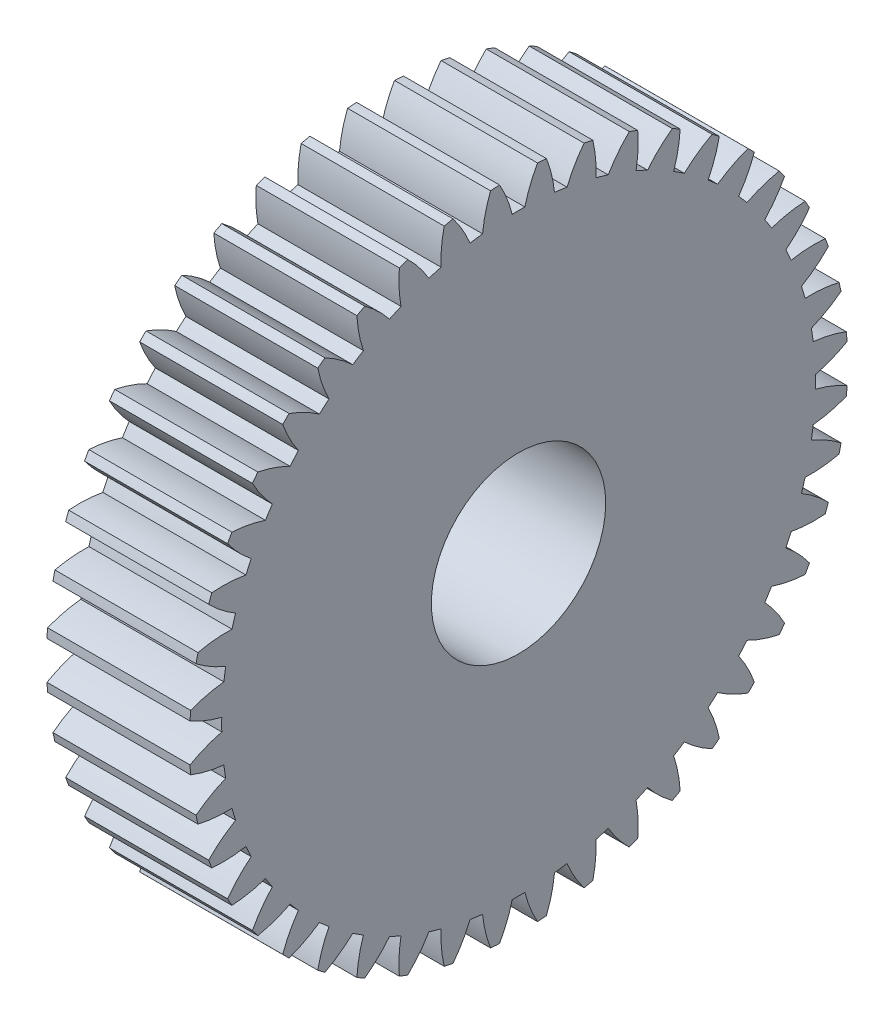
SolidWorks part; units mm, degrees
ref_plane "Plane1" through (0, 0, 0) normal (0, 0, 1) x (1, 0, 0)
ref_plane "Plane2" through (0, 0, 0) normal (0, 1, 0) x (1, 0, 0)
ref_plane "Plane3" through (0, 0, 0) normal (1, 0, 0) x (0, 0, -1)
other "Configuration Table"
sketch "HoldingSke" plane through (0, 0, 0) normal (0, 1, 0) x (1, 0, 0)
  line L0 (0, 0) -> (1.7983, -1.7366)
  line L1 (-15, 0) -> (100, 0) construction
  line L2 (0, 0) -> (-2.1039, 2.3779)
  line L3 (0, 0) -> (-11.863, 4.5341)
  line L4 (0, 0) -> (6.2122, 5.9991)
  line L5 (0, 0) -> (-46.8476, -17.4728)
  line L6 (0, 0) -> (-3.3159, -2.2372)
  line L7 (-2.1039, 2.3779) -> (8.6586, 51.2059)
  line L8 (-76.2, 54.61) -> (-76.1, 54.61)
  line L9 (-71.009, 38.7566) -> (-53.1078, 45.2721)
  line L10 (-76.2, 71.12) -> (104.1128, 71.12)
  line L11 (0, 0) -> (-4, 0)
  line L12 (-76.2, 101.6) -> (-76.185, 101.6)
  line L13 (24.9733, 27.94) -> (52.9518, 28.4284)
  line L14 (24.9733, 27.94) -> (24.9743, 27.94)
  line L15 (24.9733, 27.94) -> (100.4006, 29.5858)
  line L16 (-63.627, -0.4) -> (-12.827, -0.4)
  circle A0 centre (0, 0) radius 0.5
  circle A1 centre (0, 0) radius 8.299
  circle A2 centre (0, 0) radius 37.5
  circle A3 centre (0, 0) radius 0.5
  dimension "MHD" = 16.598
  dimension "Hub_dia" = 75
  dimension "Bore" = 1
  dimension "MBD" = 1
  dimension "Num_teeth" = 44
  dimension "Pitch" = 2.5
  dimension "Overall_len" = 50
  dimension "Show_teeth" = 44
  dimension "Thickness" = 4
  dimension "OAL" = 50.0001
  dimension "T_dim" = 0.1
  dimension "Ap" = 20
  dimension "H" = 19.05
  dimension "Pitch_radius" = 180.3128
  dimension "Width" = 4
  dimension "Backlash" = 0.015
  dimension "Addendum_fac" = 1
  dimension "Dedendum_fac" = 1.25
  dimension "Clearance_fac" = 0.25
  dimension "Dedendum_add" = 0.001
  dimension "Module" = 0.4
sketch "BasProSke" plane through (0, 0, 0) normal (0, 1, 0) x (1, 0, 0)
  line L0 (-10, 0) -> (60, 0) construction
  line L1 (0, 0) -> (0, 9.2)
  line L2 (0, 0) -> (4, 0)
  line L3 (4, 0) -> (4, 9.2)
  line L4 (4, 9.2) -> (0, 9.2)
  dimension "Thickness" = 4
  dimension "Diameter" = 18.4
revolve "Base-Revolve" add sketch "BasProSke" angle 360 about L0
sketch "TooCutSke" plane through (0, 0, 0) normal (1, 0, 0) x (0, 0, -1)
  line L1 (0, 0) -> (0, 107) construction
  line L2 (0, 0) -> (-0.3403, 8.7934) construction
  line L3 (0, 0) -> (-1.2549, 17.5458) construction
  line L4 (-0.3403, 8.7934) -> (-0.6274, 8.7729) construction
  arc A0 (0.177, 8.2971) -> (-0.177, 8.2971) centre (0, 0) ccw
  arc A1 (0.5454, 9.2093) -> (-0.5454, 9.2093) centre (0, 0) ccw
  circle A2 centre (0, 0) radius 8.8 construction
  circle A3 centre (0, 0) radius 8.2693 construction
  arc A4 (-0.177, 8.2971) -> (-0.5454, 9.2093) centre (-3.593, 7.4479) ccw
  arc A5 (0.5454, 9.2093) -> (0.177, 8.2971) centre (3.593, 7.4479) ccw
  dimension "Root_dia" = 16.598
  dimension "Overcut_dia" = 18.4508
  dimension "Pitch_dia" = 17.6
  dimension "Base_dia" = 16.5386
  dimension "Flank_rad" = 3.52
  dimension "Half_ang" = 4.091
  dimension "Half_CT" = 0.2878
extrude "ToothCut" cut sketch "TooCutSke" along normal through all
fillet "Breaks" [suppressed] radius 0.008
fillet "RootFillets" [suppressed] radius 0.101
pattern_circular "TeethCuts" count 44 every 8.182 about axis through (-10, 0, 0) along (1, 0, 0) of "ToothCut", "RootFillets", "Breaks"
sketch "HubNeaOneSke" plane through (0, 0, 0) normal (-1, 0, 0) x (0, 0, 1)
  circle A0 centre (0, 0) radius 8.299
  dimension "Diameter" = 16.598
extrude "HubNearOne" [suppressed] add sketch "HubNeaOneSke" along normal blind 46.0001
sketch "HubNeaBotSke" plane through (0, 0, 0) normal (-1, 0, 0) x (0, 0, 1)
  circle A0 centre (0, 0) radius 8.299
  dimension "Diameter" = 16.598
extrude "HubNearBoth" [suppressed] add sketch "HubNeaBotSke" along normal blind 23
ref_plane "FarPln" through (4, 0, 0) normal (1, 0, 0) x (0, 0, -1)
sketch "HubFarSke" plane through (4, 0, 0) normal (1, 0, 0) x (0, 0, -1)
  circle A0 centre (0, 0) radius 8.299
  dimension "Diameter" = 16.598
extrude "HubFar" [suppressed] add sketch "HubFarSke" along normal blind 23
sketch "BorSke" plane through (0, 0, 0) normal (1, 0, 0) x (0, 0, -1)
  circle A0 centre (0, 0) radius 0.5
  dimension "Diameter" = 1
extrude "Bore" cut sketch "BorSke" along normal mid plane 100.0001
sketch "KeySke" plane through (0, 0, 0) normal (1, 0, 0) x (0, 0, -1)
  line L0 (-0.05, 0) -> (-0.05, 0.6)
  line L1 (-0.05, 0.6) -> (0.05, 0.6)
  line L2 (0.05, 0.6) -> (0.05, 0)
  line L3 (0, 0) -> (0, 34) construction
  line L4 (-0.05, 0) -> (0.05, 0)
  dimension "Offset" = 0.6
  dimension "Width" = 0.1
extrude "Keyway" [suppressed] cut sketch "KeySke" along normal mid plane 100.0001
pattern_circular "Keyway2" [suppressed] count 2 every 90 about axis through (-10, 0, 0) along (1, 0, 0)
sketch "Sketch1" plane through (4, 0, 0) normal (1, 0, 0) x (0, 0, -1)
  circle A0 centre (0, 0) radius 2.4375
  dimension "D1" = 4.875
extrude "Cut-Extrude1" cut sketch "Sketch1" against normal through all
equation "' \"Module@HoldingSke\" = 6.35"
equation "' \"Num_teeth@HoldingSke\" = 12"
equation "' \"Ap@HoldingSke\" =  20"
equation "' \"Ap@HoldingSke\" = 20"
equation "' \"Width@HoldingSke\" = 0.5 * 25.4"
equation "' \"Hub_dia@HoldingSke\"= 1 * 25.4"
equation "' \"Hub_dia@HoldingSke\" = 1 * 25.4"
equation "' \"Overall_len@HoldingSke\" = 1.0 * 25.4"
equation "' \"Bore@HoldingSke\" = 0.75 * 25.4"
equation "' \"T_dim@HoldingSke\" = 0.1 * 25.4"
equation "' \"Width@KeySke\" = 0.25 * 25.4"
equation "' \"Show_teeth@HoldingSke\" = 13"
equation "' \"Backlash@HoldingSke\" = 0.009 * 25.4"
equation "' \"Addendum_fac@HoldingSke\" = 1.0"
equation "' \"Dedendum_fac@HoldingSke\" = 1.25"
equation "' \"Dedendum_add@HoldingSke\" = 0.00005 * 25.4"
equation "' \"Clearance_fac@HoldingSke\" = 0.25"
equation "\"Pitch@HoldingSke\" = 1 / \"Module@HoldingSke\""
equation "\"Overcut_dia@TooCutSke\" = (\"Num_teeth@HoldingSke\" + 2 * \"Addendum_fac@HoldingSke\") / \"Pitch@HoldingSke\" + 0.002 * 25.4"
equation "\"Pitch_dia@TooCutSke\" = \"Num_teeth@HoldingSke\" / \"Pitch@HoldingSke\""
equation "\"Base_dia@TooCutSke\" = \"Num_teeth@HoldingSke\" / \"Pitch@HoldingSke\" * cos((\"Ap@HoldingSke\"  * 3.14159265 / 180))"
equation "\"Root_dia@TooCutSke\" = (\"Num_teeth@HoldingSke\" + 2) / \"Pitch@HoldingSke\" - 2 * (\"Addendum_fac@HoldingSke\" + \"Dedendum_fac@HoldingSke\") / \"Pitch@HoldingSke\" - \"Dedendum_add@HoldingSke\" * 2"
equation "\"Half_ang@TooCutSke\" = 180 / \"Num_teeth@HoldingSke\""
equation "\"Half_CT@TooCutSke\" = \"Num_teeth@HoldingSke\" / \"Pitch@HoldingSke\" * sin((3.14159265 / 2 / \"Num_teeth@HoldingSke\")) / 2 - 7 * \"Backlash@HoldingSke\" / 4"
equation "\"Flank_rad@TooCutSke\" = \"Num_teeth@HoldingSke\" / \"Pitch@HoldingSke\" / 5"
equation "\"Radius@RootFillets\" = \"Clearance_fac@HoldingSke\" / \"Pitch@HoldingSke\" + \"Dedendum_add@HoldingSke\""
equation "\"Break_rad@Breaks\" = 0.02 / \"Pitch@HoldingSke\""
equation "\"Thickness@HoldingSke\" = \"Width@HoldingSke\""
equation "\"OAL@HoldingSke\" = \"Thickness@HoldingSke\""
equation "\"MHD@HoldingSke\" = (\"Num_teeth@HoldingSke\" + 2) / \"Pitch@HoldingSke\" - 2 * (\"Addendum_fac@HoldingSke\" + \"Dedendum_fac@HoldingSke\")  / \"Pitch@HoldingSke\" - \"Dedendum_add@HoldingSke\" * 2"
equation "\"MBD@HoldingSke\" = (\"Num_teeth@HoldingSke\" + 2) / \"Pitch@HoldingSke\" - 2 * (\"Addendum_fac@HoldingSke\" + \"Dedendum_fac@HoldingSke\")  / \"Pitch@HoldingSke\" - \"Dedendum_add@HoldingSke\" * 2 - 0.002 * 25.4"
equation "\"MHD@HoldingSke\" = ((sgn( \"MHD@HoldingSke\" - \"Hub_dia@HoldingSke\" )-1)*( \"MHD@HoldingSke\" - \"Hub_dia@HoldingSke\" ))/-2+ \"Hub_dia@HoldingSke\""
equation "\"MBD@HoldingSke\" = ((sgn( \"MBD@HoldingSke\" - \"Bore@HoldingSke\" )-1)*( \"MBD@HoldingSke\" - \"Bore@HoldingSke\" ))/-2+ \"Bore@HoldingSke\""
equation "\"OAL@HoldingSke\" = ((sgn( \"OAL@HoldingSke\" - \"Overall_len@HoldingSke\" )+1)*( \"OAL@HoldingSke\" - \"Overall_len@HoldingSke\" ))/2 + \"Overall_len@HoldingSke\" + 0.000002 * 25.4"
equation "\"Num_teeth@TeethCuts\" = int( \"Show_teeth@HoldingSke\" ) + 1"
equation "\"Num_teeth@TeethCuts\" = ((sgn( \"Num_teeth@TeethCuts\" - \"Num_teeth@HoldingSke\" )-1)*( \"Num_teeth@TeethCuts\" - \"Num_teeth@HoldingSke\" ))/-2+ \"Num_teeth@HoldingSke\""
equation "\"Num_teeth@TeethCuts\" = ((sgn( \"Num_teeth@TeethCuts\" - 2.0)+1)*( \"Num_teeth@TeethCuts\" - 2.0))/2 +2.0"
equation "\"Angle@TeethCuts\" = 360.0 / \"Num_teeth@HoldingSke\""
equation "\"Diameter@BasProSke\" = (\"Num_teeth@HoldingSke\" + 2 * \"Addendum_fac@HoldingSke\") / \"Pitch@HoldingSke\""
equation "\"Thickness@BasProSke\"  = \"Thickness@HoldingSke\""
equation "' \"Fillet_rad@BasProSke\" =  \"Thickness@HoldingSke\" * 0.05"
equation "' \"Fillet_rad@BasProSke\" = \"Thickness@HoldingSke\" * 0.05"
equation "\"MHD@HoldingSke\" = ((sgn( \"MHD@HoldingSke\" - \"Root_dia@TooCutSke\" )-1)*( \"MHD@HoldingSke\" - \"Root_dia@TooCutSke\" ))/-2+ \"Root_dia@TooCutSke\""
equation "\"Diameter@HubNeaOneSke\" = \"MHD@HoldingSke\""
equation "\"Length@HubNearOne\" = \"OAL@HoldingSke\" - \"Thickness@BasProSke\""
equation "\"Diameter@HubNeaBotSke\" = \"MHD@HoldingSke\""
equation "\"Length@HubNearBoth\" = ( \"OAL@HoldingSke\" - \"Thickness@BasProSke\" ) / 2.0"
equation "\"Thickness@FarPln\" = \"Thickness@BasProSke\""
equation "\"Diameter@HubFarSke\" = \"MHD@HoldingSke\""
equation "\"Length@HubFar\" = ( \"OAL@HoldingSke\" - \"Thickness@BasProSke\" ) / 2.0"
equation "\"Diameter@BorSke\" = \"MBD@HoldingSke\""
equation "\"D1@Bore\" = \"OAL@HoldingSke\" * 2.0"
equation "\"D1@Keyway\" = \"OAL@HoldingSke\" * 2.0"
equation "\"Offset@KeySke\" = \"T_dim@HoldingSke\" + \"MBD@HoldingSke\" / 2.0"
